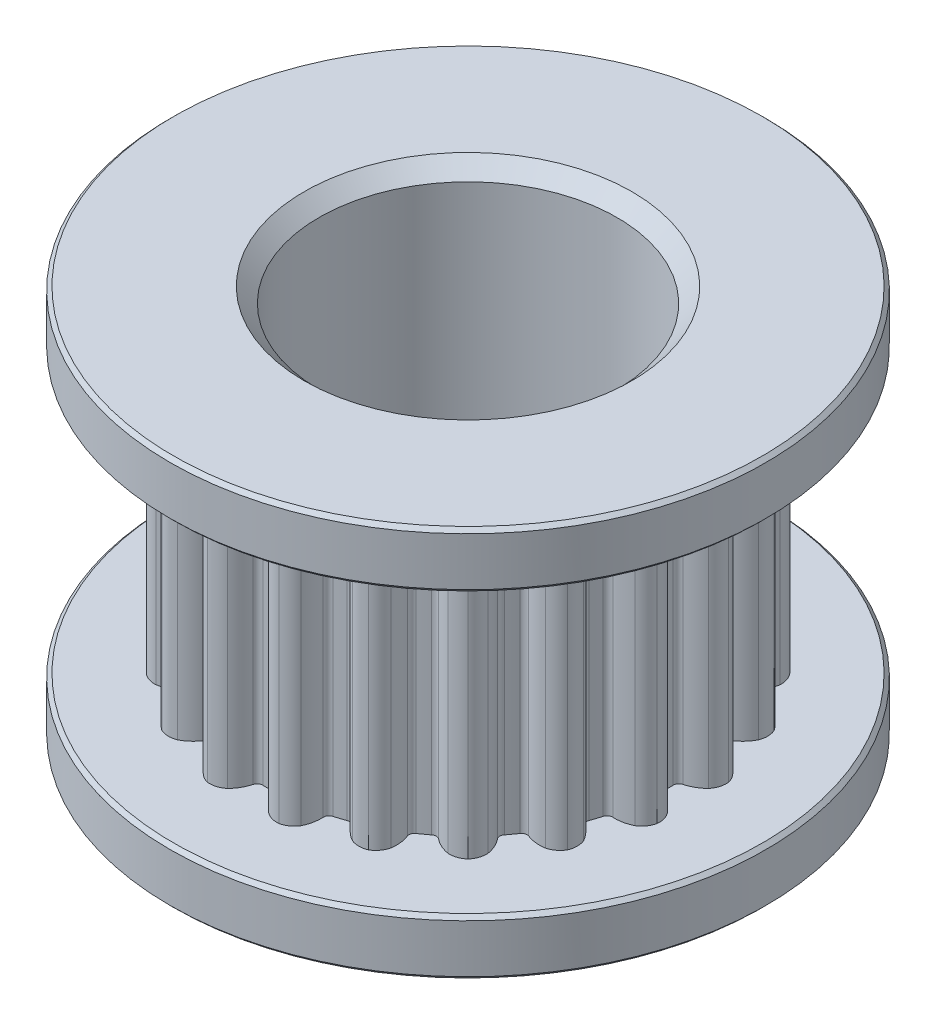
SolidWorks part; units mm, degrees
material "6061 Alloy"
ref_plane "Front Plane" through (0, 0, 0) normal (0, 0, 1) x (1, 0, 0)
ref_plane "Top Plane" through (0, 0, 0) normal (0, 1, 0) x (1, 0, 0)
ref_plane "Right Plane" through (0, 0, 0) normal (1, 0, 0) x (0, 0, -1)
sketch "BodyS" plane through (0, 0, 0) normal (0, 0, 1) x (1, 0, 0)
  line L0 (6.11, -3.75) -> (6.11, 3.75)
  line L1 (6.11, 3.75) -> (8, 3.75)
  line L2 (8, 3.75) -> (8, 5.25)
  line L3 (8, 5.25) -> (4, 5.25)
  line L4 (4, 5.25) -> (4, 2.25)
  line L5 (4, 2.25) -> (3.5, 2.25)
  line L6 (3.5, 2.25) -> (3.5, -2.25)
  line L7 (3.5, -2.25) -> (4, -2.25)
  line L8 (4, -2.25) -> (4, -5.25)
  line L9 (4, -5.25) -> (8, -5.25)
  line L10 (8, -5.25) -> (8, -3.75)
  line L11 (8, -3.75) -> (6.11, -3.75)
  line L12 (0, 0) -> (3.5, 0) construction
  line L13 (0, 5.25) -> (0, -5.25) construction
  dimension "BearingOD" = 8
  dimension "Height" = 10.5
  dimension "FlangeHeight" = 1.5
  dimension "BearingHeight" = 3
  dimension "BearingRestDiaControl" = 0.5
  dimension "RefBodyInnerDiameter" = 7
  dimension "FlangeDiaControl" = 4
  dimension "RefFlangeDia" = 16
  dimension "BeltPathDiaControl" = 2.11
  dimension "RefBeltPathDia" = 12.22
revolve "Body" add sketch "BodyS" angle 360 about L13
sketch "GT2ProfileS" plane through (0, 0, 0) normal (0, 1, 0) x (1, 0, 0)
  line L1 (0, -6.11) -> (0, -5.36) construction
  line L2 (-0.9955, -6.0283) -> (-0.8733, -5.2884) construction
  line L3 (0, 0) -> (-0.8733, -5.2884) construction
  line L4 (0.9955, -6.0283) -> (0, 0) construction
  arc A3 (0.2997, -5.4688) -> (0.1507, -5.3579) centre (0.1549, -5.5078) ccw
  arc A4 (-0.9955, -6.0283) -> (0.9955, -6.0283) centre (0, 0) ccw
  arc A5 (-0.2997, -5.4688) -> (-0.1507, -5.3579) centre (-0.1549, -5.5078) cw
  arc A6 (-0.2997, -5.4688) -> (-0.5497, -5.907) centre (-1.2653, -5.2085) cw
  circle A7 centre (0, 0) radius 6.11 construction
  arc A8 (-0.1507, -5.3579) -> (0.1507, -5.3579) centre (0, 0) ccw
  arc A9 (-0.5497, -5.907) -> (-0.9955, -6.0283) centre (-0.9051, -5.4808) cw
  arc A10 (0.2997, -5.4688) -> (0.5497, -5.907) centre (1.2653, -5.2085) ccw
  arc A11 (0.5497, -5.907) -> (0.9955, -6.0283) centre (0.9051, -5.4808) ccw
  circle A12 centre (0, 0) radius 5.36 construction
  dimension "BottomRadius" = 0.15
  dimension "MidRadius" = 1
  dimension "TopRadius" = 0.555
  dimension "Height" = 0.75
  dimension "XDistMidRadius" = 0.4
  dimension "ArcLengthAngle" = 18.755
  dimension "ArcLength" = 2
sketch "ThruBoreS" plane through (0, 0, 0) normal (0, 1, 0) x (1, 0, 0)
  circle A0 centre (0, 0) radius 4
  circle A2 centre (0, 0) radius 4 construction
extrude "ThruBore" cut sketch "ThruBoreS" against normal through all both and the other way through all
extrude "GT2Profile" cut sketch "GT2ProfileS" against normal up to surface and the other way up to surface up to face at (0, -3.75, 6.11) other way up to face at (0, 3.75, 8)
pattern_circular "GT2 Groove CP" count 20 over 360 about axis through (0, 0, 0) along (0, 1, 0) of "GT2Profile"
chamfer "InnerC" distance 0.4 angle 45 2 edges at (0, -5.25, 4) (0, 5.25, 4)
chamfer "OuterC" distance 0.1 angle 45 4 edges at (0, 5.25, 8) (0, 3.75, 8) (0, -3.75, 8) (0, -5.25, 8)
equation "\"NumTeeth@GT2 Groove CP\"=int(360/\"ArcLengthAngle@GT2ProfileS\")+1"
